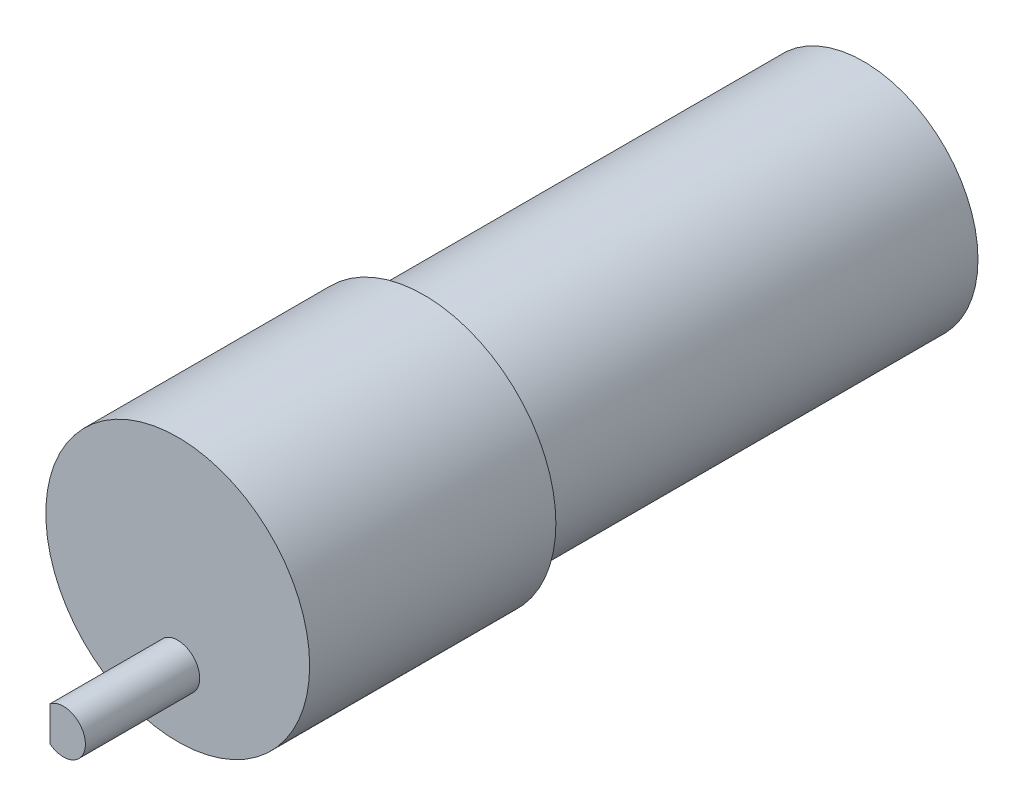
SolidWorks part; units mm, degrees
ref_plane "Front Plane" through (0, 0, 0) normal (0, 0, 1) x (1, 0, 0)
ref_plane "Top Plane" through (0, 0, 0) normal (0, 1, 0) x (1, 0, 0)
ref_plane "Right Plane" through (0, 0, 0) normal (1, 0, 0) x (0, 0, -1)
sketch "Sketch1" plane through (0, 0, 0) normal (0, 0, 1) x (1, 0, 0)
  circle A0 centre (0, 0) radius 13
  dimension "D1" = 26
extrude "Boss-Extrude1" add sketch "Sketch1" along normal blind 50
sketch "Sketch2" plane through (0, 0, 50) normal (0, 0, 1) x (1, 0, 0)
  circle A0 centre (0, 0) radius 15
  dimension "D1" = 30
extrude "Boss-Extrude2" add sketch "Sketch2" along normal blind 28
sketch "Sketch3" plane through (0, 0, 78) normal (0, 0, 1) x (1, 0, 0)
  line L0 (0, -7.5) -> (0, -5) construction
  line L1 (0, -5) -> (0, 0) construction
  circle A0 centre (0, -7.5) radius 2.5
  dimension "D1" = 5
  dimension "D2" = 5
extrude "Boss-Extrude3" add sketch "Sketch3" along normal blind 13
sketch "Sketch4" plane through (0, 0, 91) normal (0, 0, 1) x (1, 0, 0)
  line L0 (-1.5, -5.5) -> (-1.5, -9.5)
  line L1 (-1.5, -9.5) -> (-3.5, -9.5)
  line L2 (-3.5, -9.5) -> (-3.5, -5.5)
  line L3 (-3.5, -5.5) -> (-1.5, -5.5)
  circle A2 centre (0, -7.5) radius 2.5 construction
  circle A3 centre (0, -7.5) radius 2.5 construction
  dimension "D1" = 2
  dimension "D2" = 1.5
extrude "Cut-Extrude1" cut sketch "Sketch4" against normal up to surface (13 mm away) up to face at (15, 0, 78)
